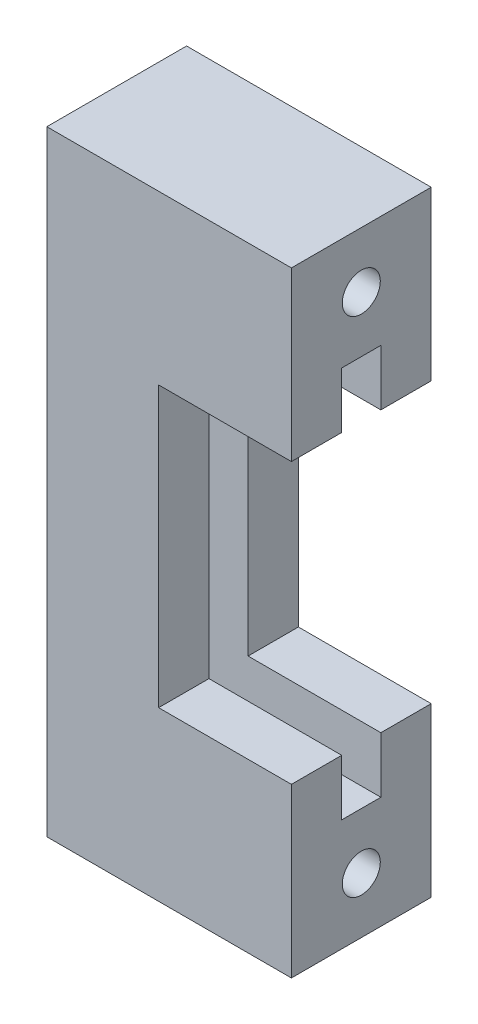
SolidWorks part; units mm, degrees
ref_plane "Front Plane" through (0, 0, 0) normal (0, 0, 1) x (1, 0, 0)
ref_plane "Top Plane" through (0, 0, 0) normal (0, 1, 0) x (1, 0, 0)
ref_plane "Right Plane" through (0, 0, 0) normal (1, 0, 0) x (0, 0, -1)
sketch "Sketch2" plane through (0, 0, 0) normal (0, 0, 1) x (1, 0, 0)
  line L1 (-45.72, 55.88) -> (0, 55.88)
  line L2 (-45.72, 55.88) -> (-45.72, 0)
  line L3 (-45.72, 0) -> (0, 0)
  line L4 (0, 55.88) -> (0, 0)
  line L5 (-40.64, 45.72) -> (-5.08, 45.72)
  line L6 (-40.64, 45.72) -> (-40.64, 10.16)
  line L7 (-40.64, 10.16) -> (-5.08, 10.16)
  line L8 (-5.08, 45.72) -> (-5.08, 10.16)
  point P8 (0, 0)
  dimension "D1" = 45.72
  dimension "D2" = 55.88
  dimension "D3" = 35.56
  dimension "D4" = 35.56
  dimension "D5" = 10.16
  dimension "D6" = 5.08
extrude "Boss-Extrude1" add sketch "Sketch2" along normal blind 12.7
sketch "Sketch3" plane through (0, 0, 0) normal (0, 0, 1) x (1, 0, 0)
  line L1 (-40.64, 45.72) -> (-5.08, 45.72)
  line L2 (-40.64, 45.72) -> (-40.64, 10.16)
  line L3 (-40.64, 10.16) -> (-5.08, 10.16)
  line L4 (-5.08, 45.72) -> (-5.08, 10.16)
extrude "Boss-Extrude2" add sketch "Sketch3" along normal blind 4.572
sketch "Sketch4" plane through (0, 0, 12.7) normal (0, 0, 1) x (1, 0, 0)
  line L0 (-40.64, 45.72) -> (-40.64, 10.16) construction
  line L1 (-40.64, 45.72) -> (-5.08, 45.72)
  line L2 (-40.64, 45.72) -> (-40.64, 10.16)
  line L3 (-40.64, 10.16) -> (-5.08, 10.16)
  line L4 (-5.08, 45.72) -> (-5.08, 10.16)
  line L5 (-40.64, 45.72) -> (-40.64, 10.16) construction
extrude "Boss-Extrude3" add sketch "Sketch4" against normal blind 4.572
sketch "Sketch5" plane through (0, 0, 12.7) normal (0, 0, 1) x (1, 0, 0)
  line L0 (0, 55.88) -> (-45.72, 55.88) construction
  line L1 (-35.56, 40.64) -> (-10.16, 40.64)
  line L2 (-35.56, 40.64) -> (-35.56, 15.24)
  line L3 (-35.56, 15.24) -> (-10.16, 15.24)
  line L4 (-10.16, 40.64) -> (-10.16, 15.24)
  line L5 (0, 0) -> (0, 55.88) construction
  dimension "D1" = 25.4
  dimension "D2" = 25.4
  dimension "D3" = 15.24
  dimension "D4" = 10.16
extrude "Cut-Extrude1" cut sketch "Sketch5" against normal through all
sketch "Sketch6" plane through (-45.72, 0, 0) normal (-1, 0, 0) x (0, 0, 1)
  line L0 (12.7, 55.88) -> (0, 55.88) construction
  line L1 (0, 55.88) -> (0, 0) construction
  circle A0 centre (6.35, 50.8) radius 1.7272
  dimension "D1" = 3.4544
  dimension "D2" = 5.08
  dimension "D3" = 6.35
extrude "Cut-Extrude2" cut sketch "Sketch6" against normal through all
sketch "Sketch7" plane through (-45.72, 0, 0) normal (-1, 0, 0) x (0, 0, 1)
  line L0 (12.7, 0) -> (0, 0) construction
  line L1 (12.7, 55.88) -> (12.7, 0) construction
  circle A0 centre (6.35, 5.08) radius 1.7272
  point P4 (0, 0)
  point P6 (24.5623, 6.7605)
  dimension "D1" = 3.4544
  dimension "D2" = 5.08
  dimension "D3" = 6.35
extrude "Cut-Extrude3" cut sketch "Sketch7" against normal through all
sketch "Sketch8" plane through (0, 0, 12.7) normal (0, 0, 1) x (1, 0, 0)
  line L0 (0, 55.88) -> (-45.72, 55.88) construction
  line L1 (-23.495, 55.88) -> (-22.225, 55.88)
  line L2 (-23.495, 55.88) -> (-23.495, 0)
  line L3 (-23.495, 0) -> (-22.225, 0)
  line L4 (-22.225, 55.88) -> (-22.225, 0)
  line L5 (-45.72, 0) -> (0, 0) construction
  line L6 (-22.86, 55.88) -> (-22.86, 31.0788) construction
  point P10 (-22.86, 55.88)
  dimension "D1" = 1.27
extrude "Cut-Extrude4" cut sketch "Sketch8" against normal through all
